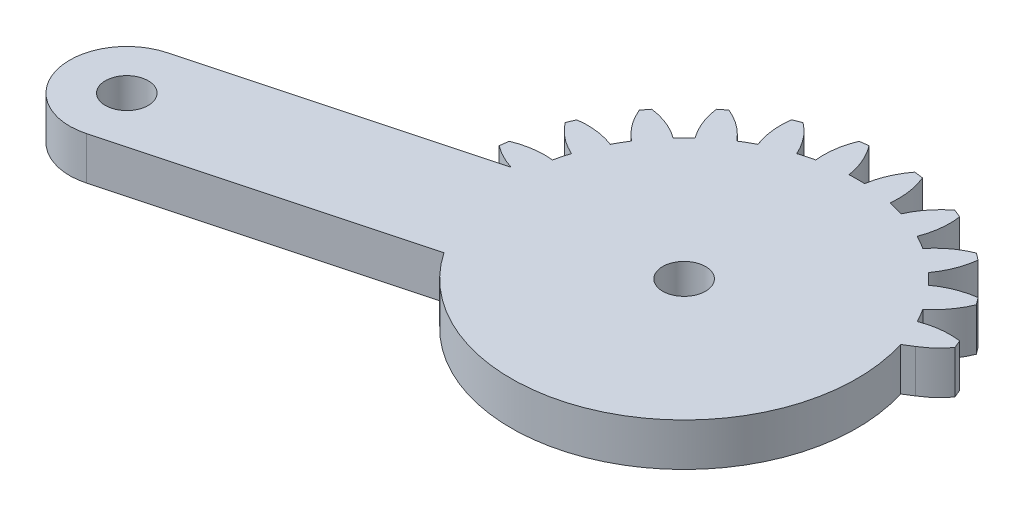
SolidWorks part; units mm, degrees
ref_plane "Front Plane" through (0, 0, 0) normal (0, 0, 1) x (1, 0, 0)
ref_plane "Top Plane" through (0, 0, 0) normal (0, 1, 0) x (1, 0, 0)
ref_plane "Right Plane" through (0, 0, 0) normal (1, 0, 0) x (0, 0, -1)
sketch "Sketch1" plane through (0, 0, 0) normal (0, 1, 0) x (1, 0, 0)
  line L0 (20.6437, 4) -> (2.0816, 4)
  line L1 (2.0816, -4) -> (20.6437, -4)
  arc A0 (2.0816, 4) -> (3.5217, 5.3071) centre (-0.7683, 8.5867) ccw
  arc A1 (3.5217, 5.3071) -> (3.2829, 5.8838) centre (-10.1063, 0) ccw
  arc A2 (3.2829, 5.8838) -> (0.6271, 5.5703) centre (2.5684, 0.5313) ccw
  arc A3 (0.6271, 5.5703) -> (0.0844, 6.5103) centre (-10.1063, 0) ccw
  arc A4 (0.0844, 6.5103) -> (1.6838, 8.6535) centre (-3.3089, 10.711) ccw
  arc A5 (1.6838, 8.6535) -> (1.3038, 9.1487) centre (-10.1063, 0) ccw
  arc A6 (1.3038, 9.1487) -> (-1.1803, 8.1585) centre (1.999, 3.7936) ccw
  arc A7 (-1.1803, 8.1585) -> (-1.9479, 8.926) centre (-10.1063, 0) ccw
  arc A8 (-1.9479, 8.926) -> (-0.9576, 11.4102) centre (-6.3127, 12.1053) ccw
  arc A9 (-0.9576, 11.4102) -> (-1.4528, 11.7901) centre (-10.1063, 0) ccw
  arc A10 (-1.4528, 11.7901) -> (-3.596, 10.1907) centre (0.6046, 6.7975) ccw
  arc A11 (-3.596, 10.1907) -> (-4.5361, 10.7334) centre (-10.1063, 0) ccw
  arc A12 (-4.5361, 10.7334) -> (-4.2225, 13.3892) centre (-9.5751, 12.6747) ccw
  arc A13 (-4.2225, 13.3892) -> (-4.7992, 13.6281) centre (-10.1063, 0) ccw
  arc A14 (-4.7992, 13.6281) -> (-6.4554, 11.5285) centre (-1.5196, 9.3381) ccw
  arc A15 (-6.4554, 11.5285) -> (-7.5039, 11.8094) centre (-10.1063, 0) ccw
  arc A16 (-7.5039, 11.8094) -> (-7.8884, 14.4558) centre (-12.8736, 12.3803) ccw
  arc A17 (-7.8884, 14.4558) -> (-8.5072, 14.5373) centre (-10.1063, 0) ccw
  arc A18 (-8.5072, 14.5373) -> (-9.5636, 12.0806) centre (-4.2291, 11.2423) ccw
  arc A19 (-9.5636, 12.0806) -> (-10.6491, 12.0806) centre (-10.1063, 0) ccw
  arc A20 (-10.6491, 12.0806) -> (-11.7054, 14.5373) centre (-15.9836, 11.2423) ccw
  arc A21 (-11.7054, 14.5373) -> (-12.3243, 14.4558) centre (-10.1063, 0) ccw
  arc A22 (-12.3243, 14.4558) -> (-12.7088, 11.8094) centre (-7.3391, 12.3803) ccw
  arc A23 (-12.7088, 11.8094) -> (-13.7573, 11.5285) centre (-10.1063, 0) ccw
  arc A24 (-13.7573, 11.5285) -> (-15.4135, 13.6281) centre (-18.6931, 9.3381) ccw
  arc A25 (-15.4135, 13.6281) -> (-15.9901, 13.3892) centre (-10.1063, 0) ccw
  arc A26 (-15.9901, 13.3892) -> (-15.6766, 10.7334) centre (-10.6376, 12.6747) ccw
  arc A27 (-15.6766, 10.7334) -> (-16.6166, 10.1907) centre (-10.1063, 0) ccw
  arc A28 (-16.6166, 10.1907) -> (-18.7599, 11.7901) centre (-20.8173, 6.7975) ccw
  arc A29 (-18.7599, 11.7901) -> (-19.255, 11.4102) centre (-10.1063, 0) ccw
  arc A30 (-19.255, 11.4102) -> (-18.2648, 8.926) centre (-13.9, 12.1053) ccw
  arc A31 (-18.2648, 8.926) -> (-19.0324, 8.1585) centre (-10.1063, 0) ccw
  arc A32 (-19.0324, 8.1585) -> (-21.5165, 9.1487) centre (-22.2117, 3.7936) ccw
  arc A33 (-21.5165, 9.1487) -> (-21.8965, 8.6535) centre (-10.1063, 0) ccw
  arc A34 (-21.8965, 8.6535) -> (-20.2971, 6.5103) centre (-16.9038, 10.711) ccw
  arc A35 (-20.2971, 6.5103) -> (-20.8398, 5.5703) centre (-10.1063, 0) ccw
  arc A36 (-20.8398, 5.5703) -> (-23.4956, 5.8838) centre (-22.7811, 0.5313) ccw
  arc A37 (-23.4956, 5.8838) -> (-23.7344, 5.3071) centre (-10.1063, 0) ccw
  arc A38 (-23.7344, 5.3071) -> (-21.6348, 3.6509) centre (-19.4444, 8.5867) ccw
  arc A39 (-21.6348, 3.6509) -> (-21.9157, 2.6025) centre (-10.1063, 0) ccw
  arc A40 (-21.9157, 2.6025) -> (-24.5622, 2.2179) centre (-22.4867, -2.7673) ccw
  arc A41 (-24.5622, 2.2179) -> (-24.6437, 1.5991) centre (-10.1063, 0) ccw
  arc A42 (-24.6437, 1.5991) -> (-22.1869, 0.5427) centre (-21.3486, 5.8773) ccw
  arc A43 (-22.1869, 0.5427) -> (-22.1869, -0.5427) centre (-10.1063, 0) ccw
  arc A44 (-22.1869, -0.5427) -> (-24.6437, -1.5991) centre (-21.3486, -5.8773) ccw
  arc A45 (-24.6437, -1.5991) -> (-24.5622, -2.2179) centre (-10.1063, 0) ccw
  arc A46 (-24.5622, -2.2179) -> (-21.9157, -2.6025) centre (-22.4867, 2.7673) ccw
  arc A47 (-21.9157, -2.6025) -> (-21.6348, -3.6509) centre (-10.1063, 0) ccw
  arc A48 (-21.6348, -3.6509) -> (-23.7344, -5.3071) centre (-19.4444, -8.5867) ccw
  arc A49 (-23.7344, -5.3071) -> (-23.4956, -5.8838) centre (-10.1063, 0) ccw
  arc A50 (-23.4956, -5.8838) -> (-20.8398, -5.5703) centre (-22.7811, -0.5313) ccw
  arc A51 (-20.8398, -5.5703) -> (-20.2971, -6.5103) centre (-10.1063, 0) ccw
  arc A52 (-20.2971, -6.5103) -> (-21.8965, -8.6535) centre (-16.9038, -10.711) ccw
  arc A53 (-21.8965, -8.6535) -> (-21.5165, -9.1487) centre (-10.1063, 0) ccw
  arc A54 (-21.5165, -9.1487) -> (-19.0324, -8.1585) centre (-22.2117, -3.7936) ccw
  arc A55 (-19.0324, -8.1585) -> (-18.2648, -8.926) centre (-10.1063, 0) ccw
  arc A56 (-18.2648, -8.926) -> (-19.255, -11.4102) centre (-13.9, -12.1053) ccw
  arc A57 (-19.255, -11.4102) -> (-18.7599, -11.7901) centre (-10.1063, 0) ccw
  arc A58 (-18.7599, -11.7901) -> (-16.6166, -10.1907) centre (-20.8173, -6.7975) ccw
  arc A59 (-16.6166, -10.1907) -> (-15.6766, -10.7334) centre (-10.1063, 0) ccw
  arc A60 (-15.6766, -10.7334) -> (-15.9901, -13.3892) centre (-10.6376, -12.6747) ccw
  arc A61 (-15.9901, -13.3892) -> (-15.4135, -13.6281) centre (-10.1063, 0) ccw
  arc A62 (-15.4135, -13.6281) -> (-13.7573, -11.5285) centre (-18.6931, -9.3381) ccw
  arc A63 (-13.7573, -11.5285) -> (-12.7088, -11.8094) centre (-10.1063, 0) ccw
  arc A64 (-12.7088, -11.8094) -> (-12.3243, -14.4558) centre (-7.3391, -12.3803) ccw
  arc A65 (-12.3243, -14.4558) -> (-11.7054, -14.5373) centre (-10.1063, 0) ccw
  arc A66 (-11.7054, -14.5373) -> (-10.6491, -12.0806) centre (-15.9836, -11.2423) ccw
  arc A67 (-10.6491, -12.0806) -> (-9.5636, -12.0806) centre (-10.1063, 0) ccw
  arc A68 (-9.5636, -12.0806) -> (-8.5072, -14.5373) centre (-4.2291, -11.2423) ccw
  arc A69 (-8.5072, -14.5373) -> (-7.8884, -14.4558) centre (-10.1063, 0) ccw
  arc A70 (-7.8884, -14.4558) -> (-7.5039, -11.8094) centre (-12.8736, -12.3803) ccw
  arc A71 (-7.5039, -11.8094) -> (-6.4554, -11.5285) centre (-10.1063, 0) ccw
  arc A72 (-6.4554, -11.5285) -> (-4.7992, -13.6281) centre (-1.5196, -9.3381) ccw
  arc A73 (-4.7992, -13.6281) -> (-4.2225, -13.3892) centre (-10.1063, 0) ccw
  arc A74 (-4.2225, -13.3892) -> (-4.5361, -10.7334) centre (-9.5751, -12.6747) ccw
  arc A75 (-4.5361, -10.7334) -> (-3.596, -10.1907) centre (-10.1063, 0) ccw
  arc A76 (-3.596, -10.1907) -> (-1.4528, -11.7901) centre (0.6046, -6.7975) ccw
  arc A77 (-1.4528, -11.7901) -> (-0.9576, -11.4102) centre (-10.1063, 0) ccw
  arc A78 (-0.9576, -11.4102) -> (-1.9479, -8.926) centre (-6.3127, -12.1053) ccw
  arc A79 (-1.9479, -8.926) -> (-1.1803, -8.1585) centre (-10.1063, 0) ccw
  arc A80 (-1.1803, -8.1585) -> (1.3038, -9.1487) centre (1.999, -3.7936) ccw
  arc A81 (1.3038, -9.1487) -> (1.6838, -8.6535) centre (-10.1063, 0) ccw
  arc A82 (1.6838, -8.6535) -> (0.0844, -6.5103) centre (-3.3089, -10.711) ccw
  arc A83 (0.0844, -6.5103) -> (0.6271, -5.5703) centre (-10.1063, 0) ccw
  arc A84 (0.6271, -5.5703) -> (3.2829, -5.8838) centre (2.5684, -0.5313) ccw
  arc A85 (3.2829, -5.8838) -> (3.5217, -5.3071) centre (-10.1063, 0) ccw
  arc A86 (3.5217, -5.3071) -> (2.0816, -4) centre (-0.7683, -8.5867) ccw
  arc A87 (20.6437, -4) -> (20.6437, 4) centre (20.6437, 0) ccw
  circle A88 centre (-10.1063, 0) radius 1.5
  circle A89 centre (20.6437, 0) radius 1.5
  dimension "D1" = 3
  dimension "D2" = 3
extrude "Boss-Extrude1" add sketch "Sketch1" along normal blind 3
sketch "Sketch3" plane through (0, 3, 0) normal (0, 1, 0) x (1, 0, 0)
  line L0 (-10.1063, 0) -> (-40.8563, 0) construction
  line L1 (-10.1063, 0) -> (-40.8563, -8.2394)
  line L2 (-11.1416, 3.8637) -> (-41.8916, -4.3757)
  line L3 (-9.0711, -3.8637) -> (-39.8211, -12.1031)
  circle A0 centre (-10.1063, 0) radius 1.5
  circle A1 centre (20.6437, 0) radius 1.5 construction
  circle A2 centre (20.6437, 0) radius 1.5
  circle A3 centre (-40.8563, -8.2394) radius 1.5
  circle A4 centre (-40.8563, -8.2394) radius 4
  circle A5 centre (-10.1063, 0) radius 4
  dimension "D2" = 3
  dimension "D5" = 3
  dimension "D6" = 8
  dimension "D7" = 8
  dimension "D1" = 30.75
  dimension "D3" = 30.75
  dimension "D4" = 15
extrude "Boss-Extrude2" add sketch "Sketch3" against normal blind 3
sketch "Sketch4" plane through (0, 3, 0) normal (0, 1, 0) x (1, 0, 0)
  line L0 (20.6437, 4) -> (2.0816, 4) construction
  line L1 (2.0816, -4) -> (20.6437, -4) construction
  line L2 (20.6437, 4) -> (2.0816, 4)
  line L3 (2.0816, -4) -> (20.6437, -4)
  line L4 (2.0816, 4) -> (1.4381, 3.6001)
  line L5 (-20.8438, -7.0182) -> (-20.0942, -6.8174)
  line L8 (-22.9143, 0.7092) -> (-41.8916, -4.3757)
  line L9 (-39.8211, -12.1031) -> (-20.8438, -7.0182)
  line L10 (2.0816, -4) -> (20.6437, -4)
  line L11 (20.6437, 4) -> (2.0816, 4)
  line L12 (-22.9143, 0.7092) -> (-41.8916, -4.3757)
  line L13 (-39.8211, -12.1031) -> (-20.8438, -7.0182)
  line L14 (2.0816, -4) -> (20.6437, -4)
  line L15 (20.6437, 4) -> (2.0816, 4)
  circle A0 centre (-10.1063, 0) radius 12.0927
  arc A1 (3.2829, 5.8838) -> (0.6271, 5.5703) centre (2.5684, 0.5313) ccw construction
  arc A2 (3.5217, 5.3071) -> (3.2829, 5.8838) centre (-10.1063, 0) ccw construction
  arc A3 (2.0816, 4) -> (3.5217, 5.3071) centre (-0.7683, 8.5867) ccw construction
  arc A4 (20.6437, -4) -> (20.6437, 4) centre (20.6437, 0) ccw construction
  arc A5 (3.5217, -5.3071) -> (2.0816, -4) centre (-0.7683, -8.5867) ccw construction
  arc A6 (3.2829, -5.8838) -> (3.5217, -5.3071) centre (-10.1063, 0) ccw construction
  arc A7 (0.6271, -5.5703) -> (3.2829, -5.8838) centre (2.5684, -0.5313) ccw construction
  arc A8 (3.2829, 5.8838) -> (0.6271, 5.5703) centre (2.5684, 0.5313) ccw
  arc A9 (3.5217, 5.3071) -> (3.2829, 5.8838) centre (-10.1063, 0) ccw
  arc A10 (2.0816, 4) -> (3.5217, 5.3071) centre (-0.7683, 8.5867) ccw
  arc A11 (20.6437, -4) -> (20.6437, 4) centre (20.6437, 0) ccw
  arc A12 (3.5217, -5.3071) -> (2.0816, -4) centre (-0.7683, -8.5867) ccw
  arc A13 (3.2829, -5.8838) -> (3.5217, -5.3071) centre (-10.1063, 0) ccw
  arc A14 (0.6271, -5.5703) -> (3.2829, -5.8838) centre (2.5684, -0.5313) ccw
  arc A95 (-24.6437, 1.5991) -> (-22.9143, 0.7092) centre (-21.3486, 5.8773) ccw
  arc A96 (-41.8916, -4.3757) -> (-39.8211, -12.1031) centre (-40.8563, -8.2394) ccw
  arc A97 (-20.8438, -7.0182) -> (-21.8965, -8.6535) centre (-16.9038, -10.711) ccw
  arc A98 (-21.8965, -8.6535) -> (-21.5165, -9.1487) centre (-10.1063, 0) ccw
  arc A99 (-21.5165, -9.1487) -> (-19.0324, -8.1585) centre (-22.2117, -3.7936) ccw
  arc A100 (-19.0324, -8.1585) -> (-18.2648, -8.926) centre (-10.1063, 0) ccw
  arc A101 (-18.2648, -8.926) -> (-19.255, -11.4102) centre (-13.9, -12.1053) ccw
  arc A102 (-19.255, -11.4102) -> (-18.7599, -11.7901) centre (-10.1063, 0) ccw
  arc A103 (-18.7599, -11.7901) -> (-16.6166, -10.1907) centre (-20.8173, -6.7975) ccw
  arc A104 (-16.6166, -10.1907) -> (-15.6766, -10.7334) centre (-10.1063, 0) ccw
  arc A105 (-15.6766, -10.7334) -> (-15.9901, -13.3892) centre (-10.6376, -12.6747) ccw
  arc A106 (-15.9901, -13.3892) -> (-15.4135, -13.6281) centre (-10.1063, 0) ccw
  arc A107 (-15.4135, -13.6281) -> (-13.7573, -11.5285) centre (-18.6931, -9.3381) ccw
  arc A108 (-13.7573, -11.5285) -> (-12.7088, -11.8094) centre (-10.1063, 0) ccw
  arc A109 (-12.7088, -11.8094) -> (-12.3243, -14.4558) centre (-7.3391, -12.3803) ccw
  arc A110 (-12.3243, -14.4558) -> (-11.7054, -14.5373) centre (-10.1063, 0) ccw
  arc A111 (-11.7054, -14.5373) -> (-10.6491, -12.0806) centre (-15.9836, -11.2423) ccw
  arc A112 (-10.6491, -12.0806) -> (-9.5636, -12.0806) centre (-10.1063, 0) ccw
  arc A113 (-9.5636, -12.0806) -> (-8.5072, -14.5373) centre (-4.2291, -11.2423) ccw
  arc A114 (-8.5072, -14.5373) -> (-7.8884, -14.4558) centre (-10.1063, 0) ccw
  arc A115 (-7.8884, -14.4558) -> (-7.5039, -11.8094) centre (-12.8736, -12.3803) ccw
  arc A116 (-7.5039, -11.8094) -> (-6.4554, -11.5285) centre (-10.1063, 0) ccw
  arc A117 (-6.4554, -11.5285) -> (-4.7992, -13.6281) centre (-1.5196, -9.3381) ccw
  arc A118 (-4.7992, -13.6281) -> (-4.2225, -13.3892) centre (-10.1063, 0) ccw
  arc A119 (-4.2225, -13.3892) -> (-4.5361, -10.7334) centre (-9.5751, -12.6747) ccw
  arc A120 (-4.5361, -10.7334) -> (-3.596, -10.1907) centre (-10.1063, 0) ccw
  arc A121 (-3.596, -10.1907) -> (-1.4528, -11.7901) centre (0.6046, -6.7975) ccw
  arc A122 (-1.4528, -11.7901) -> (-0.9576, -11.4102) centre (-10.1063, 0) ccw
  arc A123 (-0.9576, -11.4102) -> (-1.9479, -8.926) centre (-6.3127, -12.1053) ccw
  arc A124 (-1.9479, -8.926) -> (-1.1803, -8.1585) centre (-10.1063, 0) ccw
  arc A125 (-1.1803, -8.1585) -> (1.3038, -9.1487) centre (1.999, -3.7936) ccw
  arc A126 (1.3038, -9.1487) -> (1.6838, -8.6535) centre (-10.1063, 0) ccw
  arc A127 (1.6838, -8.6535) -> (0.0844, -6.5103) centre (-3.3089, -10.711) ccw
  arc A128 (0.0844, -6.5103) -> (0.6271, -5.5703) centre (-10.1063, 0) ccw
  arc A129 (0.6271, -5.5703) -> (3.2829, -5.8838) centre (2.5684, -0.5313) ccw
  arc A130 (3.2829, -5.8838) -> (3.5217, -5.3071) centre (-10.1063, 0) ccw
  arc A131 (3.5217, -5.3071) -> (2.0816, -4) centre (-0.7683, -8.5867) ccw
  arc A132 (20.6437, -4) -> (20.6437, 4) centre (20.6437, 0) ccw
  arc A133 (2.0816, 4) -> (3.5217, 5.3071) centre (-0.7683, 8.5867) ccw
  arc A134 (3.5217, 5.3071) -> (3.2829, 5.8838) centre (-10.1063, 0) ccw
  arc A135 (3.2829, 5.8838) -> (0.6271, 5.5703) centre (2.5684, 0.5313) ccw
  arc A136 (0.6271, 5.5703) -> (0.0844, 6.5103) centre (-10.1063, 0) ccw
  arc A137 (0.0844, 6.5103) -> (1.6838, 8.6535) centre (-3.3089, 10.711) ccw
  arc A138 (1.6838, 8.6535) -> (1.3038, 9.1487) centre (-10.1063, 0) ccw
  arc A139 (1.3038, 9.1487) -> (-1.1803, 8.1585) centre (1.999, 3.7936) ccw
  arc A140 (-1.1803, 8.1585) -> (-1.9479, 8.926) centre (-10.1063, 0) ccw
  arc A141 (-1.9479, 8.926) -> (-0.9576, 11.4102) centre (-6.3127, 12.1053) ccw
  arc A142 (-0.9576, 11.4102) -> (-1.4528, 11.7901) centre (-10.1063, 0) ccw
  arc A143 (-1.4528, 11.7901) -> (-3.596, 10.1907) centre (0.6046, 6.7975) ccw
  arc A144 (-3.596, 10.1907) -> (-4.5361, 10.7334) centre (-10.1063, 0) ccw
  arc A145 (-4.5361, 10.7334) -> (-4.2225, 13.3892) centre (-9.5751, 12.6747) ccw
  arc A146 (-4.2225, 13.3892) -> (-4.7992, 13.6281) centre (-10.1063, 0) ccw
  arc A147 (-4.7992, 13.6281) -> (-6.4554, 11.5285) centre (-1.5196, 9.3381) ccw
  arc A148 (-6.4554, 11.5285) -> (-7.5039, 11.8094) centre (-10.1063, 0) ccw
  arc A149 (-7.5039, 11.8094) -> (-7.8884, 14.4558) centre (-12.8736, 12.3803) ccw
  arc A150 (-7.8884, 14.4558) -> (-8.5072, 14.5373) centre (-10.1063, 0) ccw
  arc A151 (-8.5072, 14.5373) -> (-9.5636, 12.0806) centre (-4.2291, 11.2423) ccw
  arc A152 (-9.5636, 12.0806) -> (-10.6491, 12.0806) centre (-10.1063, 0) ccw
  arc A153 (-10.6491, 12.0806) -> (-11.7054, 14.5373) centre (-15.9836, 11.2423) ccw
  arc A154 (-11.7054, 14.5373) -> (-12.3243, 14.4558) centre (-10.1063, 0) ccw
  arc A155 (-12.3243, 14.4558) -> (-12.7088, 11.8094) centre (-7.3391, 12.3803) ccw
  arc A156 (-12.7088, 11.8094) -> (-13.7573, 11.5285) centre (-10.1063, 0) ccw
  arc A157 (-13.7573, 11.5285) -> (-15.4135, 13.6281) centre (-18.6931, 9.3381) ccw
  arc A158 (-15.4135, 13.6281) -> (-15.9901, 13.3892) centre (-10.1063, 0) ccw
  arc A159 (-15.9901, 13.3892) -> (-15.6766, 10.7334) centre (-10.6376, 12.6747) ccw
  arc A160 (-15.6766, 10.7334) -> (-16.6166, 10.1907) centre (-10.1063, 0) ccw
  arc A161 (-16.6166, 10.1907) -> (-18.7599, 11.7901) centre (-20.8173, 6.7975) ccw
  arc A162 (-18.7599, 11.7901) -> (-19.255, 11.4102) centre (-10.1063, 0) ccw
  arc A163 (-19.255, 11.4102) -> (-18.2648, 8.926) centre (-13.9, 12.1053) ccw
  arc A164 (-18.2648, 8.926) -> (-19.0324, 8.1585) centre (-10.1063, 0) ccw
  arc A165 (-19.0324, 8.1585) -> (-21.5165, 9.1487) centre (-22.2117, 3.7936) ccw
  arc A166 (-21.5165, 9.1487) -> (-21.8965, 8.6535) centre (-10.1063, 0) ccw
  arc A167 (-21.8965, 8.6535) -> (-20.2971, 6.5103) centre (-16.9038, 10.711) ccw
  arc A168 (-20.2971, 6.5103) -> (-20.8398, 5.5703) centre (-10.1063, 0) ccw
  arc A169 (-20.8398, 5.5703) -> (-23.4956, 5.8838) centre (-22.7811, 0.5313) ccw
  arc A170 (-23.4956, 5.8838) -> (-23.7344, 5.3071) centre (-10.1063, 0) ccw
  arc A171 (-23.7344, 5.3071) -> (-21.6348, 3.6509) centre (-19.4444, 8.5867) ccw
  arc A172 (-21.6348, 3.6509) -> (-21.9157, 2.6025) centre (-10.1063, 0) ccw
  arc A173 (-21.9157, 2.6025) -> (-24.5622, 2.2179) centre (-22.4867, -2.7673) ccw
  arc A174 (-24.5622, 2.2179) -> (-24.6437, 1.5991) centre (-10.1063, 0) ccw
  arc A175 (-24.6437, 1.5991) -> (-22.9143, 0.7092) centre (-21.3486, 5.8773) ccw
  arc A176 (-41.8916, -4.3757) -> (-39.8211, -12.1031) centre (-40.8563, -8.2394) ccw
  arc A177 (-20.8438, -7.0182) -> (-21.8965, -8.6535) centre (-16.9038, -10.711) ccw
  arc A178 (-21.8965, -8.6535) -> (-21.5165, -9.1487) centre (-10.1063, 0) ccw
  arc A179 (-21.5165, -9.1487) -> (-19.0324, -8.1585) centre (-22.2117, -3.7936) ccw
  arc A180 (-19.0324, -8.1585) -> (-18.2648, -8.926) centre (-10.1063, 0) ccw
  arc A181 (-18.2648, -8.926) -> (-19.255, -11.4102) centre (-13.9, -12.1053) ccw
  arc A182 (-19.255, -11.4102) -> (-18.7599, -11.7901) centre (-10.1063, 0) ccw
  arc A183 (-18.7599, -11.7901) -> (-16.6166, -10.1907) centre (-20.8173, -6.7975) ccw
  arc A184 (-16.6166, -10.1907) -> (-15.6766, -10.7334) centre (-10.1063, 0) ccw
  arc A185 (-15.6766, -10.7334) -> (-15.9901, -13.3892) centre (-10.6376, -12.6747) ccw
  arc A186 (-15.9901, -13.3892) -> (-15.4135, -13.6281) centre (-10.1063, 0) ccw
  arc A187 (-15.4135, -13.6281) -> (-13.7573, -11.5285) centre (-18.6931, -9.3381) ccw
  arc A188 (-13.7573, -11.5285) -> (-12.7088, -11.8094) centre (-10.1063, 0) ccw
  arc A189 (-12.7088, -11.8094) -> (-12.3243, -14.4558) centre (-7.3391, -12.3803) ccw
  arc A190 (-12.3243, -14.4558) -> (-11.7054, -14.5373) centre (-10.1063, 0) ccw
  arc A191 (-11.7054, -14.5373) -> (-10.6491, -12.0806) centre (-15.9836, -11.2423) ccw
  arc A192 (-10.6491, -12.0806) -> (-9.5636, -12.0806) centre (-10.1063, 0) ccw
  arc A193 (-9.5636, -12.0806) -> (-8.5072, -14.5373) centre (-4.2291, -11.2423) ccw
  arc A194 (-8.5072, -14.5373) -> (-7.8884, -14.4558) centre (-10.1063, 0) ccw
  arc A195 (-7.8884, -14.4558) -> (-7.5039, -11.8094) centre (-12.8736, -12.3803) ccw
  arc A196 (-7.5039, -11.8094) -> (-6.4554, -11.5285) centre (-10.1063, 0) ccw
  arc A197 (-6.4554, -11.5285) -> (-4.7992, -13.6281) centre (-1.5196, -9.3381) ccw
  arc A198 (-4.7992, -13.6281) -> (-4.2225, -13.3892) centre (-10.1063, 0) ccw
  arc A199 (-4.2225, -13.3892) -> (-4.5361, -10.7334) centre (-9.5751, -12.6747) ccw
  arc A200 (-4.5361, -10.7334) -> (-3.596, -10.1907) centre (-10.1063, 0) ccw
  arc A201 (-3.596, -10.1907) -> (-1.4528, -11.7901) centre (0.6046, -6.7975) ccw
  arc A202 (-1.4528, -11.7901) -> (-0.9576, -11.4102) centre (-10.1063, 0) ccw
  arc A203 (-0.9576, -11.4102) -> (-1.9479, -8.926) centre (-6.3127, -12.1053) ccw
  arc A204 (-1.9479, -8.926) -> (-1.1803, -8.1585) centre (-10.1063, 0) ccw
  arc A205 (-1.1803, -8.1585) -> (1.3038, -9.1487) centre (1.999, -3.7936) ccw
  arc A206 (1.3038, -9.1487) -> (1.6838, -8.6535) centre (-10.1063, 0) ccw
  arc A207 (1.6838, -8.6535) -> (0.0844, -6.5103) centre (-3.3089, -10.711) ccw
  arc A208 (0.0844, -6.5103) -> (0.6271, -5.5703) centre (-10.1063, 0) ccw
  arc A209 (0.6271, -5.5703) -> (3.2829, -5.8838) centre (2.5684, -0.5313) ccw
  arc A210 (3.2829, -5.8838) -> (3.5217, -5.3071) centre (-10.1063, 0) ccw
  arc A211 (3.5217, -5.3071) -> (2.0816, -4) centre (-0.7683, -8.5867) ccw
  arc A212 (20.6437, -4) -> (20.6437, 4) centre (20.6437, 0) ccw
  arc A213 (2.0816, 4) -> (3.5217, 5.3071) centre (-0.7683, 8.5867) ccw
  arc A214 (3.5217, 5.3071) -> (3.2829, 5.8838) centre (-10.1063, 0) ccw
  arc A215 (3.2829, 5.8838) -> (0.6271, 5.5703) centre (2.5684, 0.5313) ccw
  arc A216 (0.6271, 5.5703) -> (0.0844, 6.5103) centre (-10.1063, 0) ccw
  arc A217 (0.0844, 6.5103) -> (1.6838, 8.6535) centre (-3.3089, 10.711) ccw
  arc A218 (1.6838, 8.6535) -> (1.3038, 9.1487) centre (-10.1063, 0) ccw
  arc A219 (1.3038, 9.1487) -> (-1.1803, 8.1585) centre (1.999, 3.7936) ccw
  arc A220 (-1.1803, 8.1585) -> (-1.9479, 8.926) centre (-10.1063, 0) ccw
  arc A221 (-1.9479, 8.926) -> (-0.9576, 11.4102) centre (-6.3127, 12.1053) ccw
  arc A222 (-0.9576, 11.4102) -> (-1.4528, 11.7901) centre (-10.1063, 0) ccw
  arc A223 (-1.4528, 11.7901) -> (-3.596, 10.1907) centre (0.6046, 6.7975) ccw
  arc A224 (-3.596, 10.1907) -> (-4.5361, 10.7334) centre (-10.1063, 0) ccw
  arc A225 (-4.5361, 10.7334) -> (-4.2225, 13.3892) centre (-9.5751, 12.6747) ccw
  arc A226 (-4.2225, 13.3892) -> (-4.7992, 13.6281) centre (-10.1063, 0) ccw
  arc A227 (-4.7992, 13.6281) -> (-6.4554, 11.5285) centre (-1.5196, 9.3381) ccw
  arc A228 (-6.4554, 11.5285) -> (-7.5039, 11.8094) centre (-10.1063, 0) ccw
  arc A229 (-7.5039, 11.8094) -> (-7.8884, 14.4558) centre (-12.8736, 12.3803) ccw
  arc A230 (-7.8884, 14.4558) -> (-8.5072, 14.5373) centre (-10.1063, 0) ccw
  arc A231 (-8.5072, 14.5373) -> (-9.5636, 12.0806) centre (-4.2291, 11.2423) ccw
  arc A232 (-9.5636, 12.0806) -> (-10.6491, 12.0806) centre (-10.1063, 0) ccw
  arc A233 (-10.6491, 12.0806) -> (-11.7054, 14.5373) centre (-15.9836, 11.2423) ccw
  arc A234 (-11.7054, 14.5373) -> (-12.3243, 14.4558) centre (-10.1063, 0) ccw
  arc A235 (-12.3243, 14.4558) -> (-12.7088, 11.8094) centre (-7.3391, 12.3803) ccw
  arc A236 (-12.7088, 11.8094) -> (-13.7573, 11.5285) centre (-10.1063, 0) ccw
  arc A237 (-13.7573, 11.5285) -> (-15.4135, 13.6281) centre (-18.6931, 9.3381) ccw
  arc A238 (-15.4135, 13.6281) -> (-15.9901, 13.3892) centre (-10.1063, 0) ccw
  arc A239 (-15.9901, 13.3892) -> (-15.6766, 10.7334) centre (-10.6376, 12.6747) ccw
  arc A240 (-15.6766, 10.7334) -> (-16.6166, 10.1907) centre (-10.1063, 0) ccw
  arc A241 (-16.6166, 10.1907) -> (-18.7599, 11.7901) centre (-20.8173, 6.7975) ccw
  arc A242 (-18.7599, 11.7901) -> (-19.255, 11.4102) centre (-10.1063, 0) ccw
  arc A243 (-19.255, 11.4102) -> (-18.2648, 8.926) centre (-13.9, 12.1053) ccw
  arc A244 (-18.2648, 8.926) -> (-19.0324, 8.1585) centre (-10.1063, 0) ccw
  arc A245 (-19.0324, 8.1585) -> (-21.5165, 9.1487) centre (-22.2117, 3.7936) ccw
  arc A246 (-21.5165, 9.1487) -> (-21.8965, 8.6535) centre (-10.1063, 0) ccw
  arc A247 (-21.8965, 8.6535) -> (-20.2971, 6.5103) centre (-16.9038, 10.711) ccw
  arc A248 (-20.2971, 6.5103) -> (-20.8398, 5.5703) centre (-10.1063, 0) ccw
  arc A249 (-20.8398, 5.5703) -> (-23.4956, 5.8838) centre (-22.7811, 0.5313) ccw
  arc A250 (-23.4956, 5.8838) -> (-23.7344, 5.3071) centre (-10.1063, 0) ccw
  arc A251 (-23.7344, 5.3071) -> (-21.6348, 3.6509) centre (-19.4444, 8.5867) ccw
  arc A252 (-21.6348, 3.6509) -> (-21.9157, 2.6025) centre (-10.1063, 0) ccw
  arc A253 (-21.9157, 2.6025) -> (-24.5622, 2.2179) centre (-22.4867, -2.7673) ccw
  arc A254 (-24.5622, 2.2179) -> (-24.6437, 1.5991) centre (-10.1063, 0) ccw
  dimension "D2" = 24.1855
  dimension "D1" = 0
extrude "Cut-Extrude1" cut sketch "Sketch4" against normal blind 3 contours A178 A179 A0 L5 A177 | A182 A183 A0 A181 | A186 A187 A0 A185 | A190 A191 A0 A189 | A194 A195 A0 A193 | A198 A199 A0 A197 | A202 A203 A0 A201 | A206 A207 A0 A205 | A0 A14 A13 A12 L3 A11 L2 L4
scale "Scale1" bodies to scale 103 scale about centroid uniform scaling yes scale factor 2
